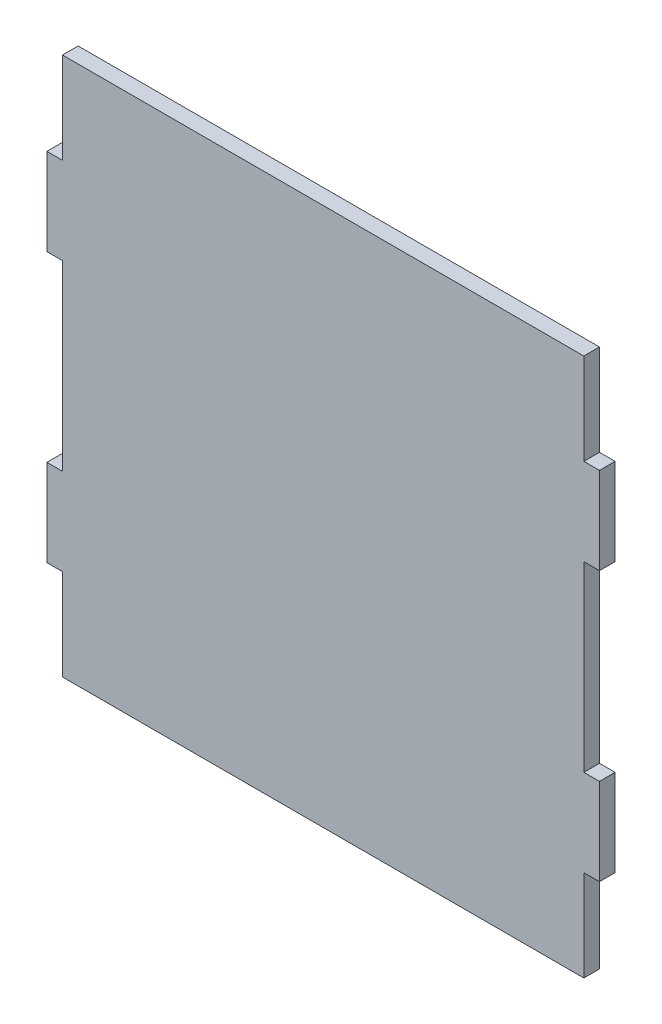
SolidWorks part; units mm, degrees
ref_plane "Front Plane" through (0, 0, 0) normal (0, 0, 1) x (1, 0, 0)
ref_plane "Top Plane" through (0, 0, 0) normal (0, 1, 0) x (1, 0, 0)
ref_plane "Right Plane" through (0, 0, 0) normal (1, 0, 0) x (0, 0, -1)
sketch "Sketch1" plane through (0, 0, 0) normal (0, 0, 1) x (1, 0, 0)
  line L0 (0, 0) -> (0, -105)
  line L5 (0, 0) -> (600, 0)
  line L6 (0, -205) -> (0, -415)
  line L7 (-18, -105) -> (0, -105)
  line L8 (-18, -105) -> (-18, -205)
  line L13 (-18, -205) -> (0, -205)
  line L21 (600, -620) -> (600, -515)
  line L25 (-18, -415) -> (0, -415)
  line L26 (-18, -515) -> (-18, -415)
  line L27 (-18, -515) -> (0, -515)
  line L28 (0, -620) -> (600, -620)
  line L29 (0, -620) -> (0, -515)
  line L30 (618, -105) -> (600, -105)
  line L31 (618, -105) -> (618, -205)
  line L32 (618, -205) -> (600, -205)
  line L33 (618, -415) -> (600, -415)
  line L34 (618, -515) -> (618, -415)
  line L35 (618, -515) -> (600, -515)
  line L36 (600, 0) -> (600, -105)
  line L37 (600, -205) -> (600, -415)
  point P2 (0, -91.1017)
  point P15 (600, -91.1017)
  point P27 (600, -368.8983)
  point P28 (0, -368.8983)
  dimension "D1" = 100
  dimension "D2" = 100
  dimension "D3" = 105
  dimension "D4" = 620
  dimension "D5" = 18
  dimension "D6" = 18
  dimension "D9" = 210
  dimension "D10" = 105
  dimension "D11" = 600
  dimension "D12" = 600
extrude "Boss-Extrude3" add sketch "Sketch1" along normal blind 18 contours L5 L36 L30 L31 L32 L37 L33 L34 L35 L21 L28 L29 L27 L26 L25 L6 L13 L8 L7 L0
